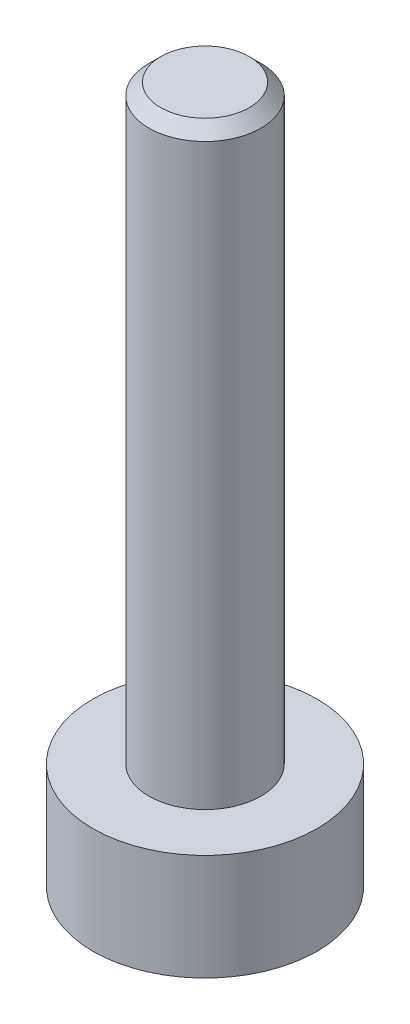
SolidWorks part; units mm, degrees
ref_plane "Front" through (0, 0, 0) normal (0, 0, 1) x (1, 0, 0)
ref_plane "Top" through (0, 0, 0) normal (0, 1, 0) x (1, 0, 0)
ref_plane "Side" through (0, 0, 0) normal (1, 0, 0) x (0, 0, -1)
sketch "Sketch1" plane through (0, 0, 0) normal (0, 0, 1) x (1, 0, 0)
  line L0 (0.95, 0) -> (1.9, 0)
  line L1 (0, 10) -> (0, -2)
  line L2 (1.5536, -2) -> (0, -2)
  line L3 (1.9, -1.8) -> (1.9, 0)
  line L4 (0, -2) -> (0, -16.7329) construction
  line L5 (0.75, 10) -> (0.95, 9.8)
  line L6 (0.75, 10) -> (0, 10)
  line L7 (0.95, 9.8) -> (0.95, 0)
  line L8 (1.5536, -2) -> (1.9, -1.8)
  dimension "D1" = 0.95
  dimension "D2" = 2
  dimension "D3" = 1.9
  dimension "D4" = 45
  dimension "D5" = 0.2
  dimension "D6" = 10
  dimension "D7" = 0.2
  dimension "D8" = 30
revolve "Base-Revolve" add sketch "Sketch1" angle 360 about L4
cosmetic thread "Cosmetic Thread1" parameters "D1"=9, "D2"=1.54
sketch "Sketch2" plane through (0, -2, 0) normal (0, -1, 0) x (1, 0, 0)
  line L0 (-0.433, 0.75) -> (0.433, 0.75)
  line L1 (0.433, 0.75) -> (0.866, 0)
  line L2 (0.866, 0) -> (0.433, -0.75)
  line L3 (0.433, -0.75) -> (-0.433, -0.75)
  line L4 (-0.433, 0.75) -> (-0.866, 0)
  line L5 (-0.866, 0) -> (-0.433, -0.75)
  line L6 (0, 0.75) -> (0, -0.75) construction
  dimension "D1" = 0.75
  dimension "D2" = 0.75
  dimension "D5" = 1.5
extrude "Cut-Extrude1" cut sketch "Sketch2" against normal blind 1
